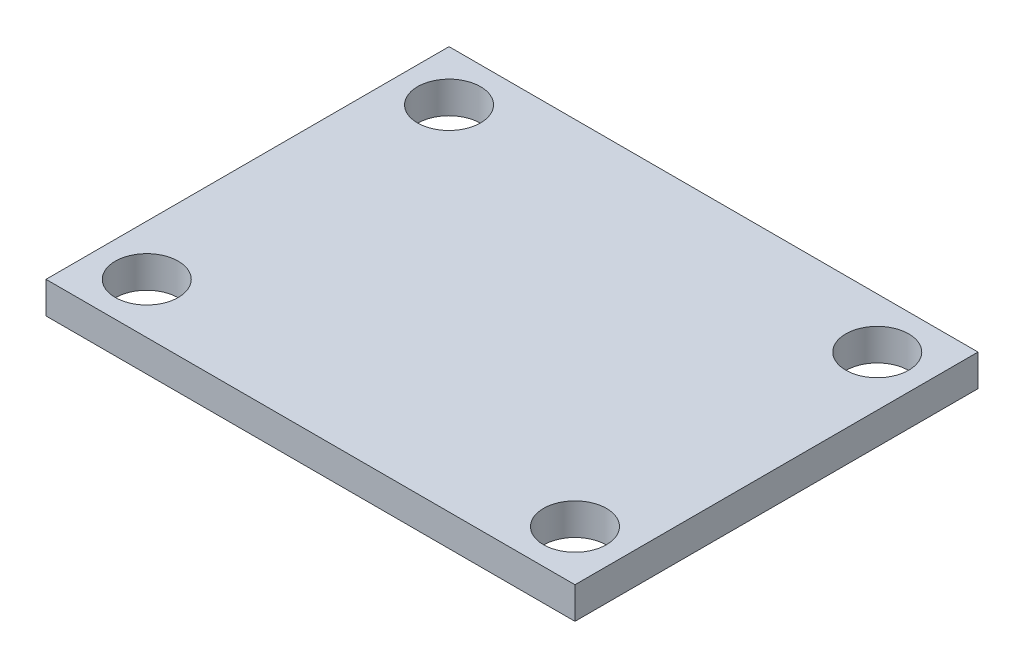
SolidWorks part; units mm, degrees
ref_plane "Front Plane" through (0, 0, 0) normal (0, 0, 1) x (1, 0, 0)
ref_plane "Top Plane" through (0, 0, 0) normal (0, 1, 0) x (1, 0, 0)
ref_plane "Right Plane" through (0, 0, 0) normal (1, 0, 0) x (0, 0, -1)
sketch "Sketch1" plane through (0, 0, 0) normal (0, 1, 0) x (1, 0, 0)
  line L1 (-13.335, -10.16) -> (13.335, -10.16)
  line L2 (-13.335, -10.16) -> (-13.335, 10.16)
  line L3 (-13.335, 10.16) -> (13.335, 10.16)
  line L4 (13.335, -10.16) -> (13.335, 10.16)
  line L5 (-13.335, -10.16) -> (13.335, 10.16) construction
  line L6 (-13.335, 10.16) -> (13.335, -10.16) construction
  line L7 (-10.795, -7.62) -> (10.795, -7.62) construction
  line L8 (-10.795, -7.62) -> (-10.795, 7.62) construction
  line L9 (-10.795, 7.62) -> (10.795, 7.62) construction
  line L10 (10.795, -7.62) -> (10.795, 7.62) construction
  line L11 (-10.795, -7.62) -> (10.795, 7.62) construction
  line L12 (-10.795, 7.62) -> (10.795, -7.62) construction
  circle A0 centre (-10.795, 7.62) radius 1.5875
  circle A1 centre (10.795, 7.62) radius 1.5875
  circle A2 centre (10.795, -7.62) radius 1.5875
  circle A3 centre (-10.795, -7.62) radius 1.5875
  point P0 (0, 0)
  point P6 (0, 0)
  dimension "D5" = 3.175
  dimension "D1" = 26.67
  dimension "D2" = 20.32
  dimension "D3" = 15.24
  dimension "D4" = 21.59
extrude "Boss-Extrude1" add sketch "Sketch1" along normal blind 1.6002
